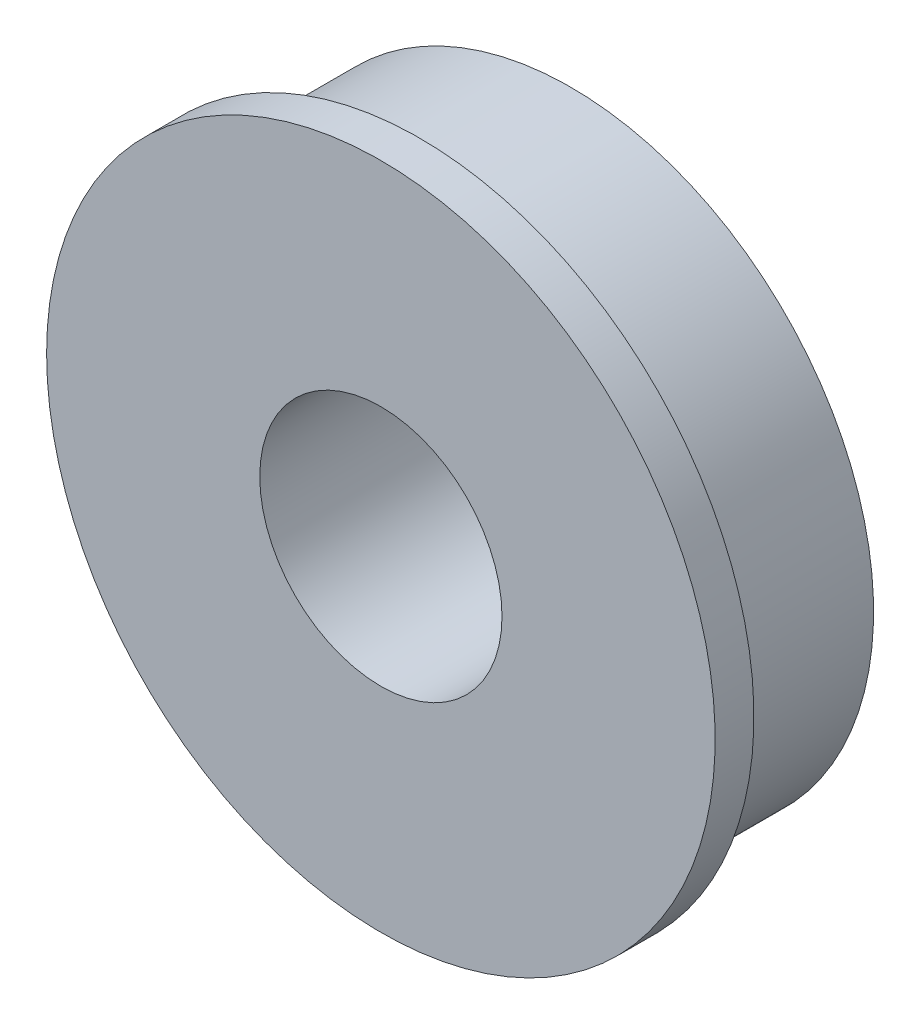
SolidWorks part; units mm, degrees
ref_plane "Front Plane" through (0, 0, 0) normal (0, 0, 1) x (1, 0, 0)
ref_plane "Top Plane" through (0, 0, 0) normal (0, 1, 0) x (1, 0, 0)
ref_plane "Right Plane" through (0, 0, 0) normal (1, 0, 0) x (0, 0, -1)
sketch "Sketch1" plane through (0, 0, 0) normal (0, 1, 0) x (1, 0, 0)
  line L0 (-38.7081, -1.5875) -> (-38.7081, 99.7956) construction
  line L1 (-38.7081, 94.0234) -> (-38.7081, 99.0018)
  line L2 (-44.2961, 95.0394) -> (-26.7701, 95.0394) construction
  line L3 (-43.4706, 99.0018) -> (-27.5956, 99.0018) construction
  line L4 (-43.4706, 95.0394) -> (-43.4706, 99.0018) construction
  line L5 (-44.2961, 95.0394) -> (-44.2961, 94.0234) construction
  line L6 (-44.2961, 94.0234) -> (-26.7701, 94.0234) construction
  line L9 (-44.2961, 95.0394) -> (-38.7081, 95.0394)
  line L10 (-43.4706, 99.0018) -> (-38.7081, 99.0018)
  line L11 (-43.4706, 95.0394) -> (-43.4706, 99.0018)
  line L12 (-44.2961, 95.0394) -> (-44.2961, 94.0234)
  line L13 (-44.2961, 94.0234) -> (-38.7081, 94.0234)
  line L14 (-43.4706, 95.0394) -> (-27.5956, 95.0394) construction
  line L15 (-43.4706, 95.0394) -> (-38.7081, 95.0394)
  line L16 (-35.5331, 99.0018) -> (-35.5331, 94.0234) construction
  line L17 (-35.5331, -1.5875) -> (-35.5331, 99.7956) construction
revolve "Revolve1" add sketch "Sketch1" angle 360 about L16
